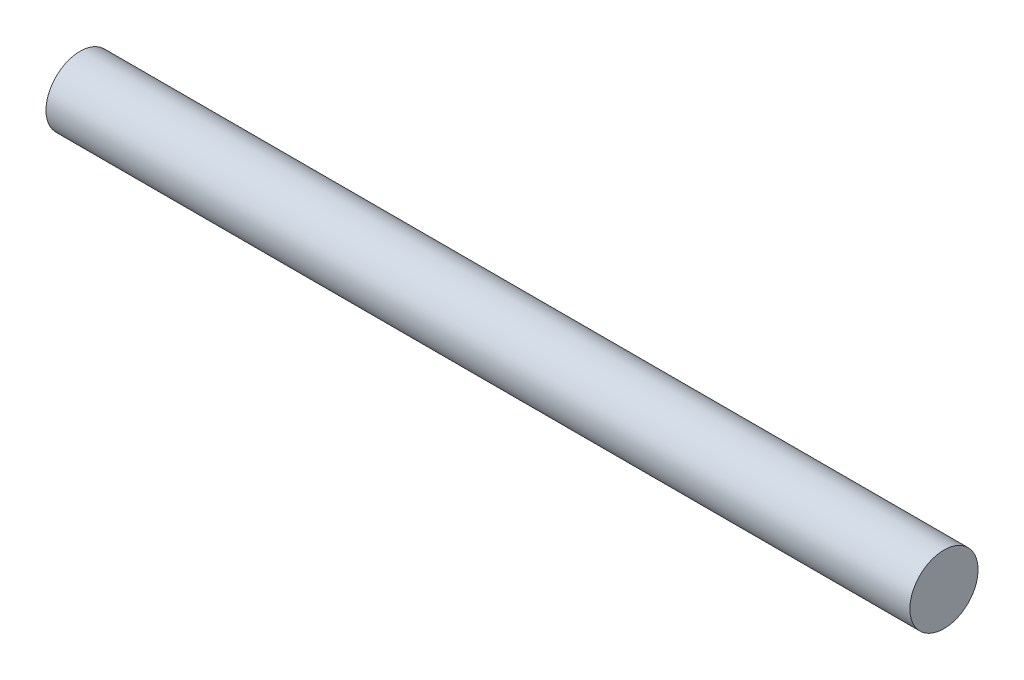
SolidWorks part; units mm, degrees
material "6061 Alloy"
ref_plane "Front Plane" through (0, 0, 0) normal (0, 0, 1) x (1, 0, 0)
ref_plane "Top Plane" through (0, 0, 0) normal (0, 1, 0) x (1, 0, 0)
ref_plane "Right Plane" through (0, 0, 0) normal (1, 0, 0) x (0, 0, -1)
sketch "Sketch1" plane through (0, 0, 0) normal (1, 0, 0) x (0, 0, -1)
  circle A1 centre (0, 0) radius 4.7625
  dimension "D1" = 9.525
extrude "Boss-Extrude1" add sketch "Sketch1" along normal blind 120.65
